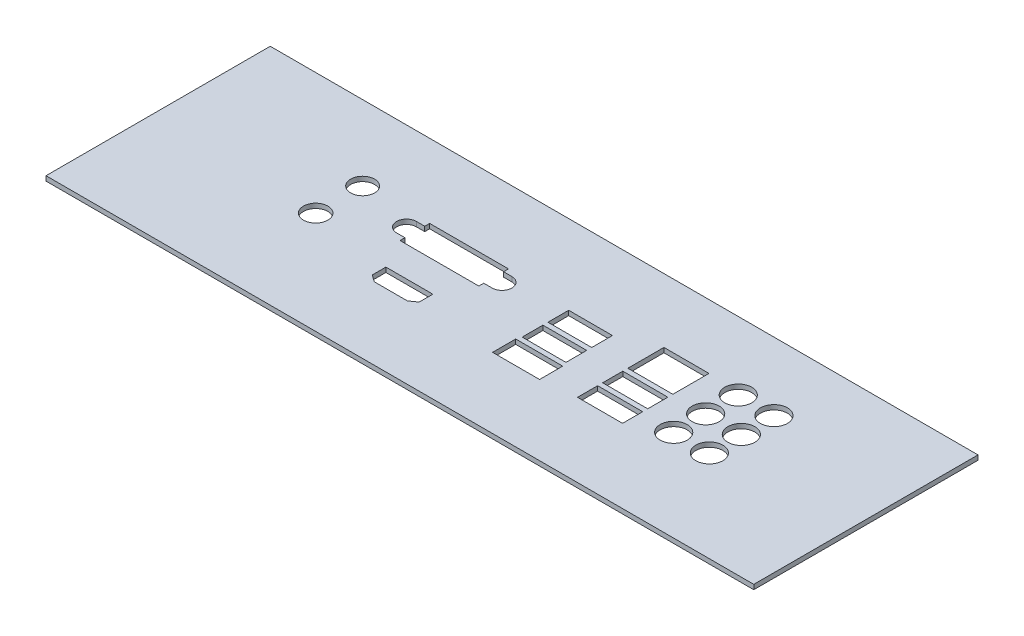
SolidWorks part; units mm, degrees
ref_plane "Front Plane" through (0, 0, 0) normal (0, 0, 1) x (1, 0, 0)
ref_plane "Top Plane" through (0, 0, 0) normal (0, 1, 0) x (1, 0, 0)
ref_plane "Right Plane" through (0, 0, 0) normal (1, 0, 0) x (0, 0, -1)
sketch "Sketch1" plane through (0, 0, 0) normal (0, 1, 0) x (1, 0, 0)
  line L0 (-119.6944, 37.9212) -> (119.6944, -37.9212) construction
  line L1 (-119.6944, 37.9212) -> (119.6944, 37.9212)
  line L2 (-119.6944, 37.9212) -> (-119.6944, -37.9212)
  line L3 (-119.6944, -37.9212) -> (119.6944, -37.9212)
  line L4 (119.6944, 37.9212) -> (119.6944, -37.9212)
  line L5 (119.6944, -37.9212) -> (120.7986, -37.5531) construction
extrude "Boss-Extrude1" add sketch "Sketch1" against normal blind 1.5875
sketch "Sketch2" plane through (0, 0, 0) normal (0, 1, 0) x (1, 0, 0)
  line B0 (-35.4463, -7.2005) -> (-19.5713, -7.2005)
  line B1 (-19.5713, -7.2005) -> (-19.5713, -11.8291)
  line B2 (-19.5713, -11.8291) -> (-21.9208, -13.4743)
  line B3 (-21.9208, -13.4743) -> (-33.0968, -13.4743)
  line B4 (-33.0968, -13.4743) -> (-35.4463, -11.8291)
  line B5 (-35.4463, -11.8291) -> (-35.4463, -7.2005)
  line B6 (-40.8438, 4.6232) -> (-40.8438, 2.9595)
  line B7 (-40.8438, 2.9595) -> (-14.1738, 2.9595)
  line B8 (-14.1738, 2.9595) -> (-14.1738, 4.6232)
  line B9 (-14.1738, 4.6232) -> (-11.3671, 4.6232)
  line B10 (-11.3671, 11.3288) -> (-14.1738, 11.3288)
  line B11 (-14.1738, 11.3288) -> (-14.1738, 12.9925)
  line B12 (-14.1738, 12.9925) -> (-40.8438, 12.9925)
  line B13 (-40.8438, 12.9925) -> (-40.8438, 11.3288)
  line B14 (-40.8438, 11.3288) -> (-43.6505, 11.3288)
  line B15 (-43.6505, 4.6232) -> (-40.8438, 4.6232)
  line B16 (8.1099, 11.06) -> (22.9181, 11.06)
  line B17 (8.1099, 11.06) -> (8.1099, 4.0496)
  line B18 (8.1099, 4.0496) -> (22.9181, 4.0496)
  line B19 (22.9181, 11.06) -> (22.9181, 4.0496)
  line B20 (8.1099, 2.3478) -> (22.9181, 2.3478)
  line B21 (8.1099, 2.3478) -> (8.1099, -4.6626)
  line B22 (8.1099, -4.6626) -> (22.9181, -4.6626)
  line B23 (22.9181, 2.3478) -> (22.9181, -4.6626)
  line B24 (7.5638, -6.3136) -> (23.4642, -6.3136)
  line B25 (7.5638, -6.3136) -> (7.5638, -14.1368)
  line B26 (7.5638, -14.1368) -> (23.4642, -14.1368)
  line B27 (23.4642, -6.3136) -> (23.4642, -14.1368)
  line B28 (35.1022, 16.2893) -> (50.3422, 16.2893)
  line B29 (35.1022, 16.2893) -> (35.1022, 4.0719)
  line B30 (35.1022, 4.0719) -> (50.3422, 4.0719)
  line B31 (50.3422, 16.2893) -> (50.3422, 4.0719)
  line B32 (35.1022, 2.3701) -> (50.3422, 2.3701)
  line B33 (35.1022, 2.3701) -> (35.1022, -4.4371)
  line B34 (35.1022, -4.4371) -> (50.3422, -4.4371)
  line B35 (50.3422, 2.3701) -> (50.3422, -4.4371)
  line B36 (35.1022, -6.1389) -> (50.3422, -6.1389)
  line B37 (35.1022, -6.1389) -> (35.1022, -12.9461)
  line B38 (35.1022, -12.9461) -> (50.3422, -12.9461)
  line B39 (50.3422, -6.1389) -> (50.3422, -12.9461)
  arc B40 (-43.6505, 11.3288) -> (-43.6505, 4.6232) centre (-43.6505, 7.976) ccw
  arc B41 (-11.3671, 4.6232) -> (-11.3671, 11.3288) centre (-11.3671, 7.976) ccw
  circle B42 centre (-63.1323, -3.2687) radius 4.1275
  circle B43 centre (61.6198, -6.9359) radius 4.572
  circle B44 centre (-63.1323, 12.6063) radius 4.0513
  circle B45 centre (61.6198, 14.9081) radius 4.572
  circle B46 centre (73.6848, 14.9081) radius 4.572
  circle B47 centre (61.6198, 3.8845) radius 4.572
  circle B48 centre (73.6848, 3.8845) radius 4.572
  circle B49 centre (73.6848, -6.9359) radius 4.572
sketch_block_instance "Block10.2-1"
sketch_block "Block10.2" parameters "D1"=8.1026, "D2"=9.144, "D3"=8.255, "D4"=6.7056, "D5"=10.033, "D6"=15.875, "D7"=6.2738, "D8"=26.67, "D9"=38.989, "D10"=35, "D11"=10.16, "D12"=11.176, "D13"=15.9004, "D14"=14.8082, "D15"=1.651, "D16"=1.7018, "D17"=7.8232, "D18"=7.0104, "D19"=1.7018, "D20"=1.7018, "D21"=12.2174, "D22"=6.8072, "D23"=15.24, "D24"=5.2293, "D25"=12.065, "D26"=10.8204, "D27"=11.0236
extrude "Cut-Extrude1" cut sketch "Sketch2" against normal through all
